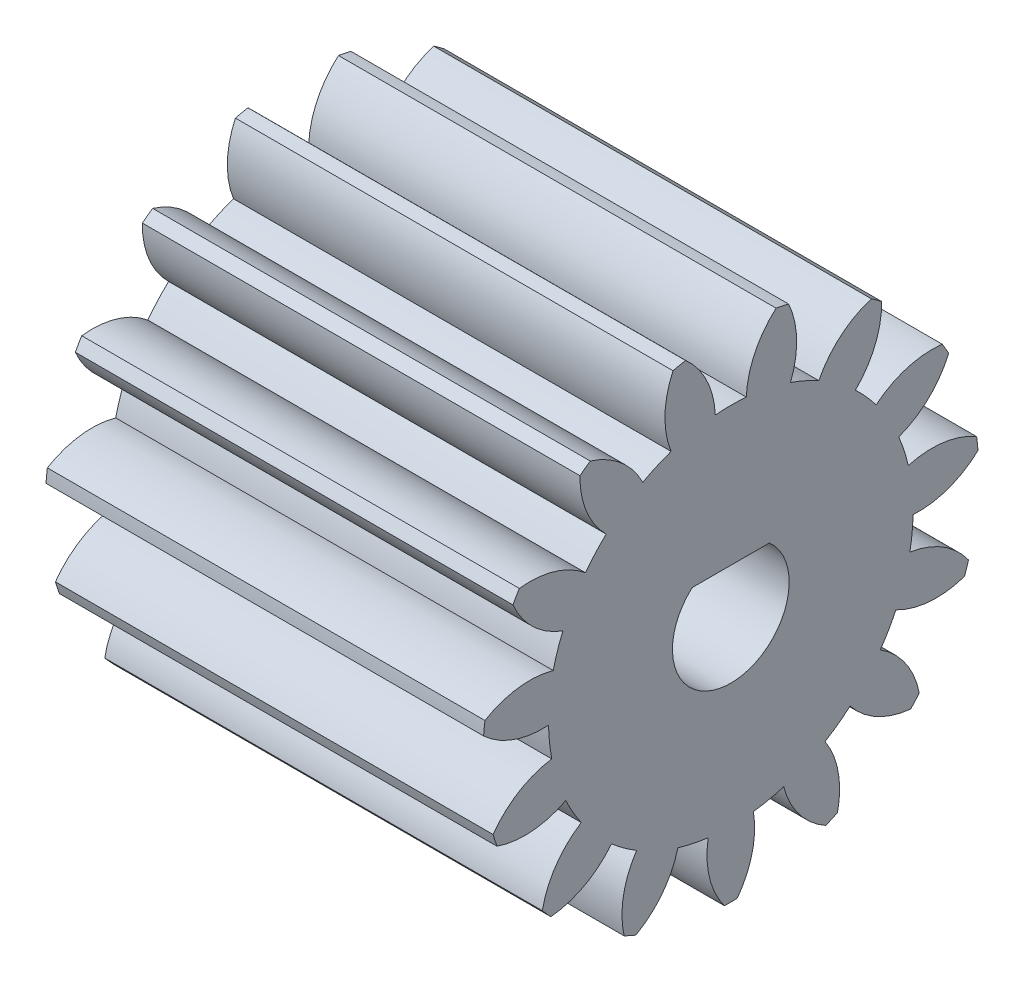
SolidWorks part; units mm, degrees
ref_plane "Plane1" through (0, 0, 0) normal (0, 0, 1) x (1, 0, 0)
ref_plane "Plane2" through (0, 0, 0) normal (0, 1, 0) x (1, 0, 0)
ref_plane "Plane3" through (0, 0, 0) normal (1, 0, 0) x (0, 0, -1)
sketch "HoldingSke" plane through (0, 0, 0) normal (0, 1, 0) x (1, 0, 0)
  line L0 (0, 0) -> (0.9659, -0.2588)
  line L1 (-15, 0) -> (100, 0) construction
  line L2 (0, 0) -> (-2.1039, 2.3779)
  line L3 (0, 0) -> (-11.863, 4.5341)
  line L4 (0, 0) -> (8.3417, 2.2352)
  line L5 (0, 0) -> (-46.8476, -17.4728)
  line L6 (0, 0) -> (-12.4344, -8.3896)
  line L7 (-2.1039, 2.3779) -> (8.6586, 51.2059)
  line L8 (-76.2, 54.61) -> (-75.5, 54.61)
  line L9 (-71.009, 38.7566) -> (-53.1078, 45.2721)
  line L10 (-76.2, 71.12) -> (104.1128, 71.12)
  line L11 (0, 0) -> (-15, 0)
  line L12 (-76.2, 101.6) -> (-76.162, 101.6)
  line L13 (24.9733, 27.94) -> (52.9518, 28.4284)
  line L14 (24.9733, 27.94) -> (24.9743, 27.94)
  line L15 (24.9733, 27.94) -> (100.4006, 29.5858)
  line L16 (-63.627, -1) -> (-12.827, -1)
  circle A0 centre (0, 0) radius 2
  circle A1 centre (0, 0) radius 6.249
  circle A2 centre (0, 0) radius 37.5
  circle A3 centre (0, 0) radius 2
  dimension "MHD" = 12.498
  dimension "Hub_dia" = 75
  dimension "Bore" = 4
  dimension "MBD" = 4
  dimension "Num_teeth" = 15
  dimension "Pitch" = 1
  dimension "Overall_len" = 50
  dimension "Show_teeth" = 15
  dimension "Thickness" = 15
  dimension "OAL" = 50.0001
  dimension "T_dim" = 0.7
  dimension "Ap" = 20
  dimension "H" = 19.05
  dimension "Pitch_radius" = 180.3128
  dimension "Width" = 15
  dimension "Backlash" = 0.038
  dimension "Addendum_fac" = 1
  dimension "Dedendum_fac" = 1.25
  dimension "Clearance_fac" = 0.25
  dimension "Dedendum_add" = 0.001
  dimension "Module" = 1
sketch "BasProSke" plane through (0, 0, 0) normal (0, 1, 0) x (1, 0, 0)
  line L0 (-10, 0) -> (60, 0) construction
  line L1 (0, 0) -> (0, 8.5)
  line L2 (0, 0) -> (15, 0)
  line L3 (15, 0) -> (15, 8.5)
  line L4 (15, 8.5) -> (0, 8.5)
  dimension "Thickness" = 15
  dimension "Diameter" = 17
revolve "Base-Revolve" add sketch "BasProSke" angle 360 about L0
sketch "TooCutSke" plane through (0, 0, 0) normal (1, 0, 0) x (0, 0, -1)
  line L1 (0, 0) -> (0, 107) construction
  line L2 (0, 0) -> (-0.8504, 7.4516) construction
  line L3 (0, 0) -> (-3.1044, 14.6049) construction
  line L4 (-0.8504, 7.4516) -> (-1.5522, 7.3025) construction
  arc A0 (0.5316, 6.2263) -> (-0.5316, 6.2263) centre (0, 0) ccw
  arc A1 (1.5766, 8.3784) -> (-1.5766, 8.3784) centre (0, 0) ccw
  circle A2 centre (0, 0) radius 7.5 construction
  circle A3 centre (0, 0) radius 7.0477 construction
  arc A4 (-0.5316, 6.2263) -> (-1.5766, 8.3784) centre (-3.5289, 6.1005) ccw
  arc A5 (1.5766, 8.3784) -> (0.5316, 6.2263) centre (3.5289, 6.1005) ccw
  dimension "Root_dia" = 12.498
  dimension "Overcut_dia" = 17.0508
  dimension "Pitch_dia" = 15
  dimension "Base_dia" = 14.0954
  dimension "Flank_rad" = 3
  dimension "Half_ang" = 12
  dimension "Half_CT" = 0.7175
extrude "ToothCut" cut sketch "TooCutSke" along normal through all
fillet "Breaks" [suppressed] radius 0.02
fillet "RootFillets" [suppressed] radius 0.251
pattern_circular "TeethCuts" count 15 every 24 about axis through (-10, 0, 0) along (1, 0, 0) of "ToothCut", "RootFillets", "Breaks"
sketch "HubNeaOneSke" plane through (0, 0, 0) normal (-1, 0, 0) x (0, 0, 1)
  circle A0 centre (0, 0) radius 6.249
  dimension "Diameter" = 12.498
extrude "HubNearOne" [suppressed] add sketch "HubNeaOneSke" along normal blind 35.0001
sketch "HubNeaBotSke" plane through (0, 0, 0) normal (-1, 0, 0) x (0, 0, 1)
  circle A0 centre (0, 0) radius 6.249
  dimension "Diameter" = 12.498
extrude "HubNearBoth" [suppressed] add sketch "HubNeaBotSke" along normal blind 17.5
ref_plane "FarPln" through (15, 0, 0) normal (1, 0, 0) x (0, 0, -1)
sketch "HubFarSke" plane through (15, 0, 0) normal (1, 0, 0) x (0, 0, -1)
  circle A0 centre (0, 0) radius 6.249
  dimension "Diameter" = 12.498
extrude "HubFar" [suppressed] add sketch "HubFarSke" along normal blind 17.5
sketch "BorSke" plane through (0, 0, 0) normal (1, 0, 0) x (0, 0, -1)
  circle A0 centre (0, 0) radius 2
  dimension "Diameter" = 4
extrude "Bore" cut sketch "BorSke" along normal mid plane 100.0001
sketch "KeySke" plane through (0, 0, 0) normal (1, 0, 0) x (0, 0, -1)
  line L0 (-0.8, 0) -> (-0.8, 2.7)
  line L1 (-0.8, 2.7) -> (0.8, 2.7)
  line L2 (0.8, 2.7) -> (0.8, 0)
  line L3 (0, 0) -> (0, 34) construction
  line L4 (-0.8, 0) -> (0.8, 0)
  dimension "Offset" = 2.7
  dimension "Width" = 1.6
extrude "Keyway" [suppressed] cut sketch "KeySke" along normal mid plane 100.0001
pattern_circular "Keyway2" [suppressed] count 2 every 90 about axis through (-10, 0, 0) along (1, 0, 0)
sketch "Sketch1" plane through (15, 0, 0) normal (1, 0, 0) x (0, 0, -1)
  line L0 (0, -2) -> (0, 1.5) construction
  line L1 (-1.3229, 1.5) -> (1.3229, 1.5)
  circle A0 centre (0, 0) radius 2 construction
  arc A1 (-1.3229, 1.5) -> (1.3229, 1.5) centre (0, 0) cw
extrude "Boss-Extrude1" add sketch "Sketch1" against normal blind 15 contours A1 L1
equation "' \"Module@HoldingSke\" = 6.35"
equation "' \"Num_teeth@HoldingSke\" = 12"
equation "' \"Ap@HoldingSke\" =  20"
equation "' \"Ap@HoldingSke\" = 20"
equation "' \"Width@HoldingSke\" = 0.5 * 25.4"
equation "' \"Hub_dia@HoldingSke\"= 1 * 25.4"
equation "' \"Hub_dia@HoldingSke\" = 1 * 25.4"
equation "' \"Overall_len@HoldingSke\" = 1.0 * 25.4"
equation "' \"Bore@HoldingSke\" = 0.75 * 25.4"
equation "' \"T_dim@HoldingSke\" = 0.1 * 25.4"
equation "' \"Width@KeySke\" = 0.25 * 25.4"
equation "' \"Show_teeth@HoldingSke\" = 13"
equation "' \"Backlash@HoldingSke\" = 0.009 * 25.4"
equation "' \"Addendum_fac@HoldingSke\" = 1.0"
equation "' \"Dedendum_fac@HoldingSke\" = 1.25"
equation "' \"Dedendum_add@HoldingSke\" = 0.00005 * 25.4"
equation "' \"Clearance_fac@HoldingSke\" = 0.25"
equation "\"Pitch@HoldingSke\" = 1 / \"Module@HoldingSke\""
equation "\"Overcut_dia@TooCutSke\" = (\"Num_teeth@HoldingSke\" + 2 * \"Addendum_fac@HoldingSke\") / \"Pitch@HoldingSke\" + 0.002 * 25.4"
equation "\"Pitch_dia@TooCutSke\" = \"Num_teeth@HoldingSke\" / \"Pitch@HoldingSke\""
equation "\"Base_dia@TooCutSke\" = \"Num_teeth@HoldingSke\" / \"Pitch@HoldingSke\" * cos((\"Ap@HoldingSke\"  * 3.14159265 / 180))"
equation "\"Root_dia@TooCutSke\" = (\"Num_teeth@HoldingSke\" + 2) / \"Pitch@HoldingSke\" - 2 * (\"Addendum_fac@HoldingSke\" + \"Dedendum_fac@HoldingSke\") / \"Pitch@HoldingSke\" - \"Dedendum_add@HoldingSke\" * 2"
equation "\"Half_ang@TooCutSke\" = 180 / \"Num_teeth@HoldingSke\""
equation "\"Half_CT@TooCutSke\" = \"Num_teeth@HoldingSke\" / \"Pitch@HoldingSke\" * sin((3.14159265 / 2 / \"Num_teeth@HoldingSke\")) / 2 - 7 * \"Backlash@HoldingSke\" / 4"
equation "\"Flank_rad@TooCutSke\" = \"Num_teeth@HoldingSke\" / \"Pitch@HoldingSke\" / 5"
equation "\"Radius@RootFillets\" = \"Clearance_fac@HoldingSke\" / \"Pitch@HoldingSke\" + \"Dedendum_add@HoldingSke\""
equation "\"Break_rad@Breaks\" = 0.02 / \"Pitch@HoldingSke\""
equation "\"Thickness@HoldingSke\" = \"Width@HoldingSke\""
equation "\"OAL@HoldingSke\" = \"Thickness@HoldingSke\""
equation "\"MHD@HoldingSke\" = (\"Num_teeth@HoldingSke\" + 2) / \"Pitch@HoldingSke\" - 2 * (\"Addendum_fac@HoldingSke\" + \"Dedendum_fac@HoldingSke\")  / \"Pitch@HoldingSke\" - \"Dedendum_add@HoldingSke\" * 2"
equation "\"MBD@HoldingSke\" = (\"Num_teeth@HoldingSke\" + 2) / \"Pitch@HoldingSke\" - 2 * (\"Addendum_fac@HoldingSke\" + \"Dedendum_fac@HoldingSke\")  / \"Pitch@HoldingSke\" - \"Dedendum_add@HoldingSke\" * 2 - 0.002 * 25.4"
equation "\"MHD@HoldingSke\" = ((sgn( \"MHD@HoldingSke\" - \"Hub_dia@HoldingSke\" )-1)*( \"MHD@HoldingSke\" - \"Hub_dia@HoldingSke\" ))/-2+ \"Hub_dia@HoldingSke\""
equation "\"MBD@HoldingSke\" = ((sgn( \"MBD@HoldingSke\" - \"Bore@HoldingSke\" )-1)*( \"MBD@HoldingSke\" - \"Bore@HoldingSke\" ))/-2+ \"Bore@HoldingSke\""
equation "\"OAL@HoldingSke\" = ((sgn( \"OAL@HoldingSke\" - \"Overall_len@HoldingSke\" )+1)*( \"OAL@HoldingSke\" - \"Overall_len@HoldingSke\" ))/2 + \"Overall_len@HoldingSke\" + 0.000002 * 25.4"
equation "\"Num_teeth@TeethCuts\" = int( \"Show_teeth@HoldingSke\" ) + 1"
equation "\"Num_teeth@TeethCuts\" = ((sgn( \"Num_teeth@TeethCuts\" - \"Num_teeth@HoldingSke\" )-1)*( \"Num_teeth@TeethCuts\" - \"Num_teeth@HoldingSke\" ))/-2+ \"Num_teeth@HoldingSke\""
equation "\"Num_teeth@TeethCuts\" = ((sgn( \"Num_teeth@TeethCuts\" - 2.0)+1)*( \"Num_teeth@TeethCuts\" - 2.0))/2 +2.0"
equation "\"Angle@TeethCuts\" = 360.0 / \"Num_teeth@HoldingSke\""
equation "\"Diameter@BasProSke\" = (\"Num_teeth@HoldingSke\" + 2 * \"Addendum_fac@HoldingSke\") / \"Pitch@HoldingSke\""
equation "\"Thickness@BasProSke\"  = \"Thickness@HoldingSke\""
equation "' \"Fillet_rad@BasProSke\" =  \"Thickness@HoldingSke\" * 0.05"
equation "' \"Fillet_rad@BasProSke\" = \"Thickness@HoldingSke\" * 0.05"
equation "\"MHD@HoldingSke\" = ((sgn( \"MHD@HoldingSke\" - \"Root_dia@TooCutSke\" )-1)*( \"MHD@HoldingSke\" - \"Root_dia@TooCutSke\" ))/-2+ \"Root_dia@TooCutSke\""
equation "\"Diameter@HubNeaOneSke\" = \"MHD@HoldingSke\""
equation "\"Length@HubNearOne\" = \"OAL@HoldingSke\" - \"Thickness@BasProSke\""
equation "\"Diameter@HubNeaBotSke\" = \"MHD@HoldingSke\""
equation "\"Length@HubNearBoth\" = ( \"OAL@HoldingSke\" - \"Thickness@BasProSke\" ) / 2.0"
equation "\"Thickness@FarPln\" = \"Thickness@BasProSke\""
equation "\"Diameter@HubFarSke\" = \"MHD@HoldingSke\""
equation "\"Length@HubFar\" = ( \"OAL@HoldingSke\" - \"Thickness@BasProSke\" ) / 2.0"
equation "\"Diameter@BorSke\" = \"MBD@HoldingSke\""
equation "\"D1@Bore\" = \"OAL@HoldingSke\" * 2.0"
equation "\"D1@Keyway\" = \"OAL@HoldingSke\" * 2.0"
equation "\"Offset@KeySke\" = \"T_dim@HoldingSke\" + \"MBD@HoldingSke\" / 2.0"
